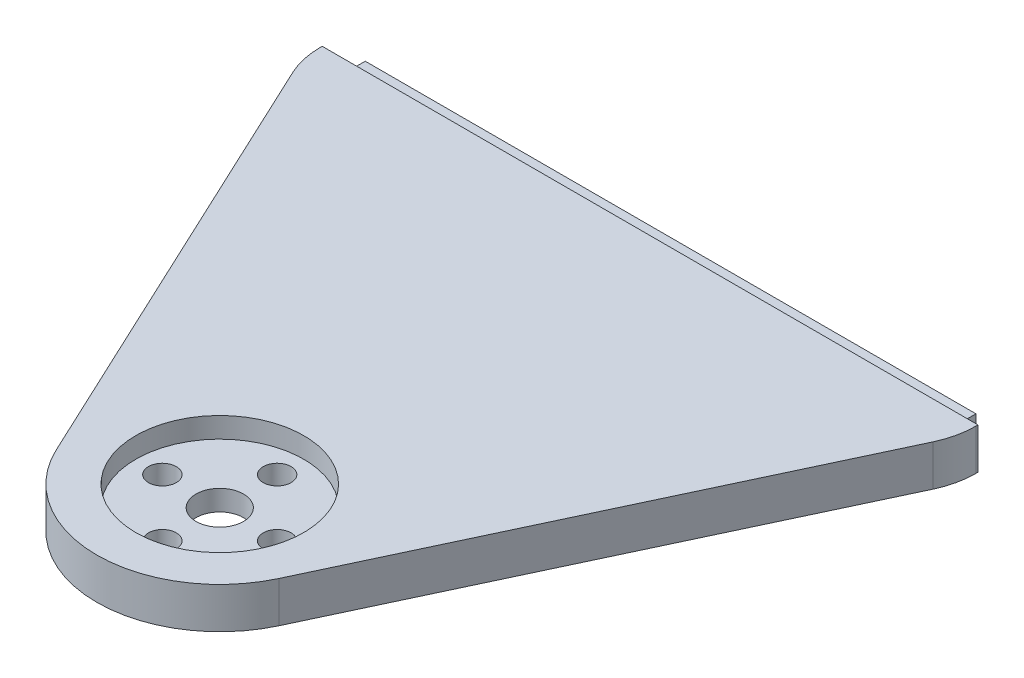
SolidWorks part; units mm, degrees
ref_plane "Front Plane" through (0, 0, 0) normal (0, 0, 1) x (1, 0, 0)
ref_plane "Top Plane" through (0, 0, 0) normal (0, 1, 0) x (1, 0, 0)
ref_plane "Right Plane" through (0, 0, 0) normal (1, 0, 0) x (0, 0, -1)
sketch "Sketch2" plane through (0, 0, 0) normal (0, 1, 0) x (1, 0, 0)
  line L0 (-40, 0) -> (40, 0)
  line L1 (-40, 0) -> (-13.5822, -56.3658)
  line L2 (40, 0) -> (13.5822, -56.3658)
  arc A0 (-13.5822, -56.3658) -> (13.5822, -56.3658) centre (0, -50) ccw
  point P4 (0, 0)
  dimension "D2" = 30
  dimension "D1" = 80
  dimension "D3" = 50
extrude "Boss-Extrude1" add sketch "Sketch2" along normal blind 5 contours L1 A0 L2 L0
sketch "Sketch3" plane through (0, 0, 0) normal (0, 0, -1) x (-1, 0, 0)
  line L1 (-40, 5) -> (40, 5)
  line L2 (-40, 5) -> (-40, 0)
  line L3 (-40, 0) -> (40, 0)
  line L4 (40, 5) -> (40, 0)
extrude "Boss-Extrude2" add sketch "Sketch3" along normal blind 5 contours L1 L4 L3 L2
sketch "Sketch6" plane through (0, 0, -5) normal (0, 0, -1) x (-1, 0, 0)
  line L1 (-40, 5) -> (40, 5)
  line L2 (-40, 5) -> (-40, 0)
  line L3 (-40, 0) -> (40, 0)
  line L4 (40, 5) -> (40, 0)
  line L5 (-37.25, 3.55) -> (37.25, 3.55)
  line L6 (-37.25, 3.55) -> (-37.25, 1.45)
  line L7 (-37.25, 1.45) -> (37.25, 1.45)
  line L8 (37.25, 3.55) -> (37.25, 1.45)
  line L9 (-37.25, 3.55) -> (37.25, 1.45) construction
  line L10 (-37.25, 1.45) -> (37.25, 3.55) construction
  point P6 (0, 2.5)
  dimension "D1" = 74.5
  dimension "D2" = 2.1
  dimension "D3" = 0
  dimension "D4" = 2.5
extrude "Cut-Extrude2" cut sketch "Sketch6" against normal blind 2.5
fillet "Fillet1" radius 10 2 edges at (-40, 2.5, 0) (40, 2.5, 0)
sketch "Sketch7" plane through (0, 0, 0) normal (0, -1, 0) x (-1, 0, 0)
  circle A0 centre (0, -50) radius 2.9
  dimension "D1" = 5.8
extrude "Cut-Extrude3" cut sketch "Sketch7" against normal blind 5
sketch "Sketch8" plane through (0, 5, 0) normal (0, 1, 0) x (1, 0, 0)
  circle A0 centre (0, -57) radius 1.7
  circle A1 centre (0, -50) radius 2.9 construction
  dimension "D1" = 3.4
  dimension "D2" = 7
extrude "Cut-Extrude4" cut sketch "Sketch8" against normal blind 5
pattern_circular "CirPattern1" count 4 over 360 about axis through (0, 0, 50) along (0, 1, 0) of "Cut-Extrude4"
sketch "Sketch9" plane through (0, 5, 0) normal (0, 1, 0) x (1, 0, 0)
  circle A0 centre (0, -50) radius 10.25
  dimension "D1" = 20.5
extrude "Cut-Extrude5" cut sketch "Sketch9" against normal blind 2.5
